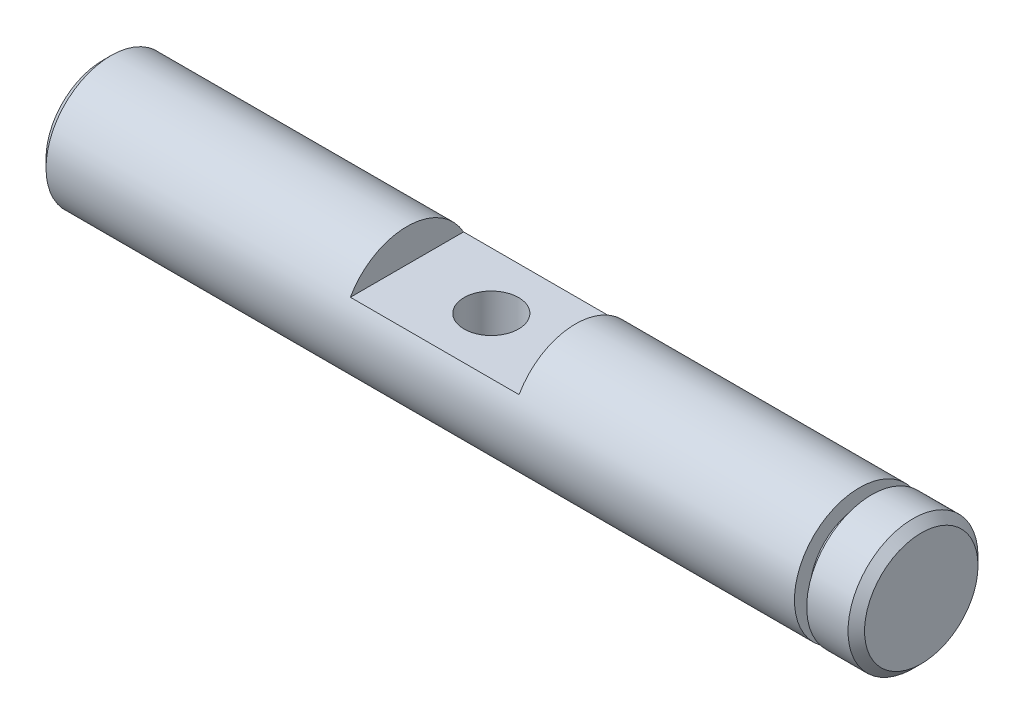
SolidWorks part; units mm, degrees
material "1.4000 (X6Cr13)"
ref_plane "Alzado" through (0, 0, 0) normal (1, 0, 0) x (0, 1, 0)
ref_plane "Planta" through (0, 0, 0) normal (0, 0, 1) x (0, 1, 0)
ref_plane "Vista lateral" through (0, 0, 0) normal (0, 1, 0) x (-1, 0, 0)
sketch "Croquis1" plane through (0, 0, 0) normal (0, 0, 1) x (0, 1, 0)
  line L0 (0, 0) -> (0, 49.5) construction
  line L1 (0, 0) -> (3.93, 0)
  line L2 (3.93, 0) -> (3.93, 3)
  line L3 (3.93, 3) -> (3, 3)
  line L4 (3, 3) -> (3, 3.74)
  line L5 (3, 3.74) -> (3.93, 3.74)
  line L6 (3.93, 3.74) -> (3.93, 49.5)
  line L7 (3.93, 49.5) -> (0, 49.5)
  line L8 (0, 0) -> (0, 49.5)
  point P4 (0, 0)
  point P11 (0, 0)
  dimension "D1" = 49.5
  dimension "D2" = 7.86
  dimension "D3" = 6
  dimension "D4" = 0.74
  dimension "D5" = 3
revolve "Revolución1" add sketch "Croquis1" angle 360 about L0
chamfer "Chaflán1" distance 0.5 angle 45 2 edges at (-49.5, 0, -3.93) (0, 0, -3.93)
ref_plane "Plano1" through (-31.1, 0, 0) normal (-1, 0, 0) x (0, 0, 1)
sketch "Croquis2" plane through (-31.1, 0, 0) normal (-1, 0, 0) x (0, 0, 1)
  line L0 (-3.4234, 1.93) -> (3.4234, 1.93)
  circle A0 centre (0, 0) radius 3.93 construction
  arc A1 (3.4234, 1.93) -> (-3.4234, 1.93) centre (0, 0) ccw
  point P4 (0, 3.93)
  dimension "D1" = 2
extrude "Cortar-Extruir1" cut sketch "Croquis2" against normal blind 10.2
sketch "Croquis3" plane through (0, 1.93, 0) normal (0, 1, 0) x (-1, 0, 0)
  line L0 (20.9, -3.4234) -> (20.9, 3.4234) construction
  line L1 (20.9, 0) -> (31.1, 0) construction
  line L2 (31.1, -3.773) -> (31.1, 3.773) construction
  line L3 (26, 3.4234) -> (26, -3.4234) construction
  line L4 (20.9, 3.4234) -> (31.1, 3.4234) construction
  line L5 (20.9, -3.4234) -> (31.1, -3.4234) construction
  point P0 (26, 0)
  point P14 (0, 0)
  point P15 (27.1763, 0.7431)
  point P16 (0, 0)
  point P17 (0, 0)
hole_wizard "Taladro roscado M4x0.71" positions "Croquis3" profile "Croquis4" tap size "M4x0.7" standard "Ansi Metric" end condition through all
sketch "Croquis4" plane through (-26, 1.93, 0) normal (1, 0, 0) x (0, 0, 1)
  line L0 (0, 0) -> (0, 5.86)
  line L1 (0, 5.86) -> (1.65, 5.86)
  line L2 (1.65, 5.86) -> (1.65, 0)
  line L5 (1.65, 0) -> (0, 0)
  line L11 (0, -6.35) -> (0, 107.95) construction
  dimension "Diámetro de perforador para roscar hasta el siguiente" = 3.3
  dimension "Profundidad de perforador para roscar hasta el siguiente" = 5.86
cosmetic thread "Rosca de taladro1" parameters "D2"=4
